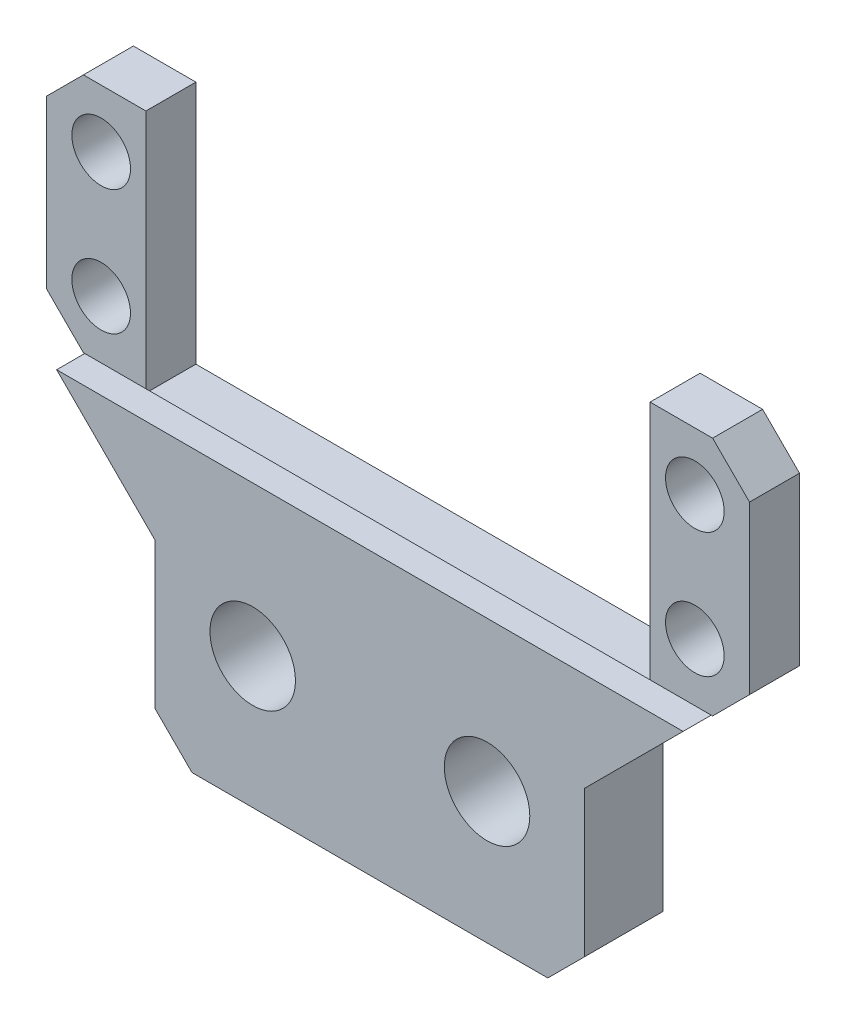
SolidWorks part; units mm, degrees
ref_plane "Front Plane" through (0, 0, 0) normal (0, 0, 1) x (1, 0, 0)
ref_plane "Top Plane" through (0, 0, 0) normal (0, 1, 0) x (1, 0, 0)
ref_plane "Right Plane" through (0, 0, 0) normal (1, 0, 0) x (0, 0, -1)
sketch "Sketch1" plane through (0, 0, 0) normal (0, 0, 1) x (1, 0, 0)
  line L0 (-17.4625, -10.541) -> (17.4625, -10.541) construction
  line L1 (17.4625, -21.209) -> (-17.4625, -21.209)
  line L2 (17.4625, -21.209) -> (17.4625, 1.651)
  line L3 (17.4625, 21.209) -> (-17.4625, 21.209)
  line L4 (-17.4625, -21.209) -> (-17.4625, 1.651)
  line L5 (17.4625, -21.209) -> (-17.4625, 21.209) construction
  line L6 (17.4625, 21.209) -> (-17.4625, -21.209) construction
  line L7 (0, 21.209) -> (0, -21.209) construction
  line L8 (-17.4625, 1.651) -> (17.4625, 1.651) construction
  line L9 (-17.4625, 6.35) -> (17.4625, 6.35) construction
  line L10 (-17.4625, 11.43) -> (17.4625, 11.43) construction
  line L11 (-17.4625, 11.43) -> (-17.4625, 1.651) construction
  line L12 (-17.4625, 5.4539) -> (-17.4625, 6.35)
  line L13 (28.575, 1.651) -> (17.4625, 1.651)
  line L14 (28.575, 1.651) -> (28.575, 21.209)
  line L15 (28.575, 21.209) -> (-28.575, 21.209)
  line L16 (-28.575, 1.651) -> (-28.575, 21.209)
  line L17 (28.575, 1.651) -> (-28.575, 21.209) construction
  line L18 (28.575, 21.209) -> (-28.575, 1.651) construction
  line L19 (17.4625, 5.4539) -> (17.4625, 6.35)
  line L20 (1.3594, 1.651) -> (-1.3594, 1.651)
  line L21 (-17.4625, 1.651) -> (-28.575, 1.651)
  circle A0 centre (-9.525, -10.541) radius 3.475
  circle A1 centre (9.525, -10.541) radius 3.475
  circle A2 centre (-24.13, 6.35) radius 2.3828
  circle A3 centre (-24.13, 16.51) radius 2.3828
  circle A4 centre (24.13, 16.51) radius 2.3828
  circle A5 centre (24.13, 6.35) radius 2.3828
  point P0 (0, 0)
  point P28 (0, 11.43)
  dimension "D4" = 9.525
  dimension "D7" = 9.779
  dimension "D1" = 34.925
  dimension "D2" = 42.418
  dimension "D3" = 10.668
  dimension "D5" = 22.86
  dimension "D6" = 4.699
  dimension "D8" = 24.13
  dimension "D9" = 57.15
extrude "Boss-Extrude1" add sketch "Sketch1" along normal blind 6.35
chamfer "Chamfer1" distance 3 angle 45 6 edges at (28.575, 21.209, 3.175) (28.575, 1.651, 3.175) (-28.575, 1.651, 3.175) (-28.575, 21.209, 3.175) (-17.4625, -21.209, 3.175) (17.4625, -21.209, 3.175)
chamfer "Chamfer2" distance 8 angle 45 2 edges at (-17.4625, 1.651, 3.175) (17.4625, 1.651, 3.175)
sketch "Sketch3" plane through (0, 0, 6.35) normal (0, 0, 1) x (1, 0, 0)
  line L0 (-25.4625, 1.651) -> (25.4625, 1.651)
  line L16 (-17.4625, -6.349) -> (-17.4625, -18.209)
  line L18 (-14.4625, -21.209) -> (14.4625, -21.209)
  line L19 (-17.4625, -18.209) -> (-14.4625, -21.209)
  line L20 (17.4625, -18.209) -> (17.4625, -6.349)
  line L21 (17.4625, -6.349) -> (25.4625, 1.651)
  line L22 (25.4625, 1.651) -> (25.575, 1.651)
  line L23 (25.575, 1.651) -> (28.575, 4.651)
  line L24 (28.575, 4.651) -> (28.575, 18.209)
  line L25 (28.575, 18.209) -> (25.575, 21.209)
  line L26 (25.575, 21.209) -> (-25.575, 21.209)
  line L27 (-25.575, 21.209) -> (-28.575, 18.209)
  line L28 (-28.575, 18.209) -> (-28.575, 4.651)
  line L29 (-28.575, 4.651) -> (-25.575, 1.651)
  line L30 (-25.575, 1.651) -> (-25.4625, 1.651)
  line L31 (-25.4625, 1.651) -> (-17.4625, -6.349)
  line L33 (14.4625, -21.209) -> (17.4625, -18.209)
  line L38 (25.4625, 1.651) -> (25.575, 1.651)
  line L39 (25.575, 1.651) -> (28.575, 4.651)
  line L40 (28.575, 4.651) -> (28.575, 18.209)
  line L41 (28.575, 18.209) -> (25.575, 21.209)
  line L42 (25.575, 21.209) -> (-25.575, 21.209)
  line L43 (-25.575, 21.209) -> (-28.575, 18.209)
  line L44 (-28.575, 18.209) -> (-28.575, 4.651)
  line L45 (-28.575, 4.651) -> (-25.575, 1.651)
  line L46 (-25.575, 1.651) -> (-25.4625, 1.651)
  dimension "D1" = 0
extrude "Cut-Extrude1" cut sketch "Sketch3" against normal blind 2.286
sketch "Sketch4" plane through (0, 0, 4.064) normal (0, 0, 1) x (1, 0, 0)
  line L0 (-28.575, 11.43) -> (28.575, 11.43) construction
  line L1 (-28.575, 18.209) -> (-28.575, 4.651) construction
  line L2 (28.575, 4.651) -> (28.575, 18.209) construction
  line L4 (20.493, 1.351) -> (-20.493, 1.351)
  line L5 (20.493, 1.351) -> (20.493, 21.509)
  line L6 (20.493, 21.509) -> (-20.493, 21.509)
  line L7 (-20.493, 1.351) -> (-20.493, 21.509)
  line L8 (20.493, 1.351) -> (-20.493, 21.509) construction
  line L9 (20.493, 21.509) -> (-20.493, 1.351) construction
  point P6 (0, 11.43)
  dimension "D1" = 40.986
  dimension "D2" = 20.158
extrude "Cut-Extrude2" cut sketch "Sketch4" against normal through all
